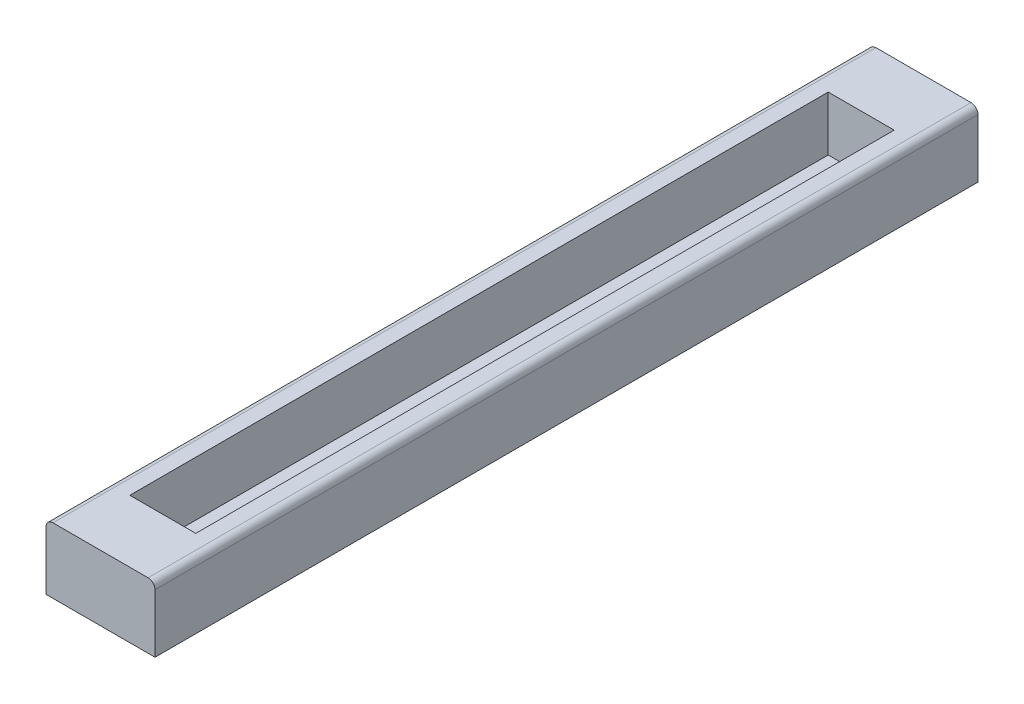
SolidWorks part; units mm, degrees
ref_plane "Front Plane" through (0, 0, 0) normal (0, 0, 1) x (1, 0, 0)
ref_plane "Top Plane" through (0, 0, 0) normal (0, 1, 0) x (1, 0, 0)
ref_plane "Right Plane" through (0, 0, 0) normal (1, 0, 0) x (0, 0, -1)
ref_plane "Plane1" through (0, 1.2, 0) normal (0, 1, 0) x (-1, 0, 0)
sketch "Sketch1" plane through (0, 1.2, 0) normal (0, 1, 0) x (-1, 0, 0)
  line L0 (-1, -7.55) -> (1, -7.55)
  line L1 (1, -7.55) -> (1, 7.55)
  line L2 (1, 7.55) -> (-1, 7.55)
  line L3 (-1, 7.55) -> (-1, -7.55)
extrude "Boss-Extrude1" add sketch "Sketch1" against normal blind 1.2
sketch "Sketch2" plane through (0, 1.2, 0) normal (0, 1, 0) x (-1, 0, 0)
  line L0 (-0.605, -6.407) -> (0.605, -6.407)
  line L1 (0.605, -6.407) -> (0.605, 6.407)
  line L2 (0.605, 6.407) -> (-0.605, 6.407)
  line L3 (-0.605, 6.407) -> (-0.605, -6.407)
extrude "Cut-Extrude1" cut sketch "Sketch2" against normal blind 1
fillet "Fillet1" radius 0.127 2 edges at (1, 1.2, 0) (-1, 1.2, 0)
